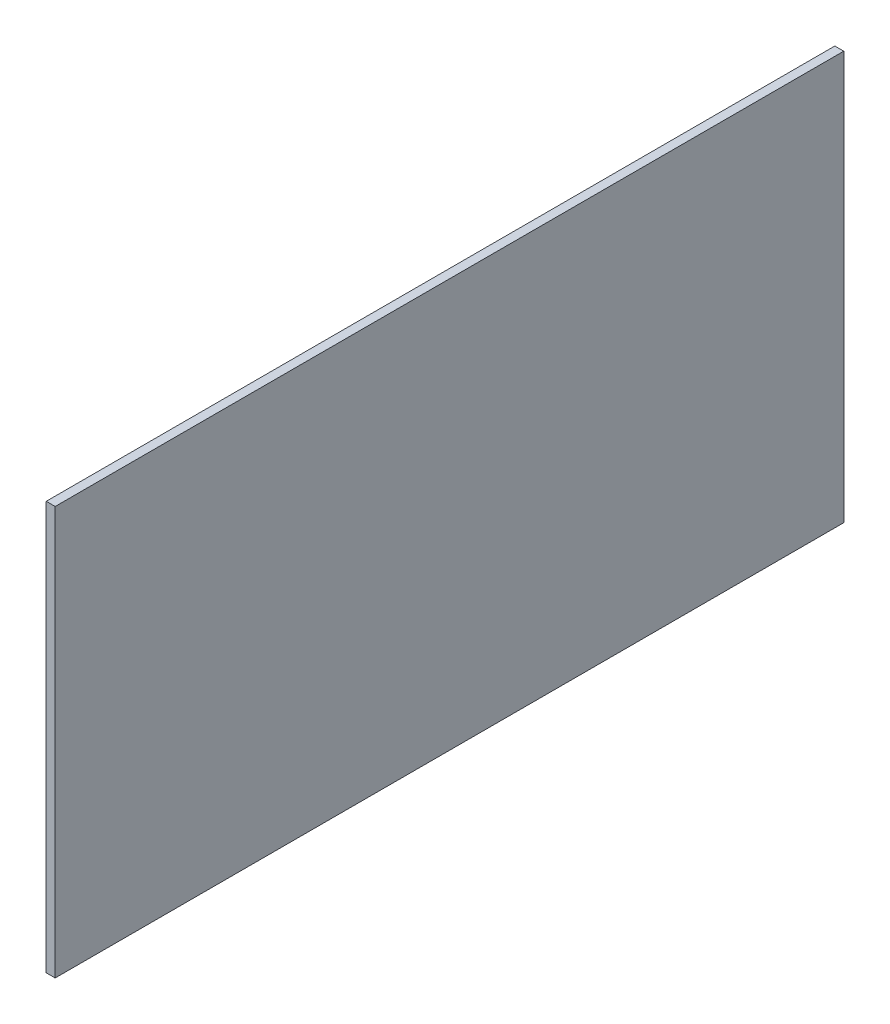
SolidWorks part; units mm, degrees
material "Oak"
ref_plane "Plan de face" through (0, 0, 0) normal (0, 0, 1) x (1, 0, 0)
ref_plane "Plan de dessus" through (0, 0, 0) normal (0, 1, 0) x (1, 0, 0)
ref_plane "Plan de droite" through (0, 0, 0) normal (1, 0, 0) x (0, 0, -1)
sketch "Esquisse1" plane through (0, 0, 0) normal (1, 0, 0) x (0, 0, -1)
  line L1 (-140, 72.5) -> (140, 72.5)
  line L2 (-140, 72.5) -> (-140, -72.5)
  line L3 (-140, -72.5) -> (140, -72.5)
  line L4 (140, 72.5) -> (140, -72.5)
  point P4 (0, 72.5)
  point P6 (140, 0)
  dimension "D1" = 280
  dimension "D2" = 145
extrude "Boss.-Extru.1" add sketch "Esquisse1" along normal blind 3.175
